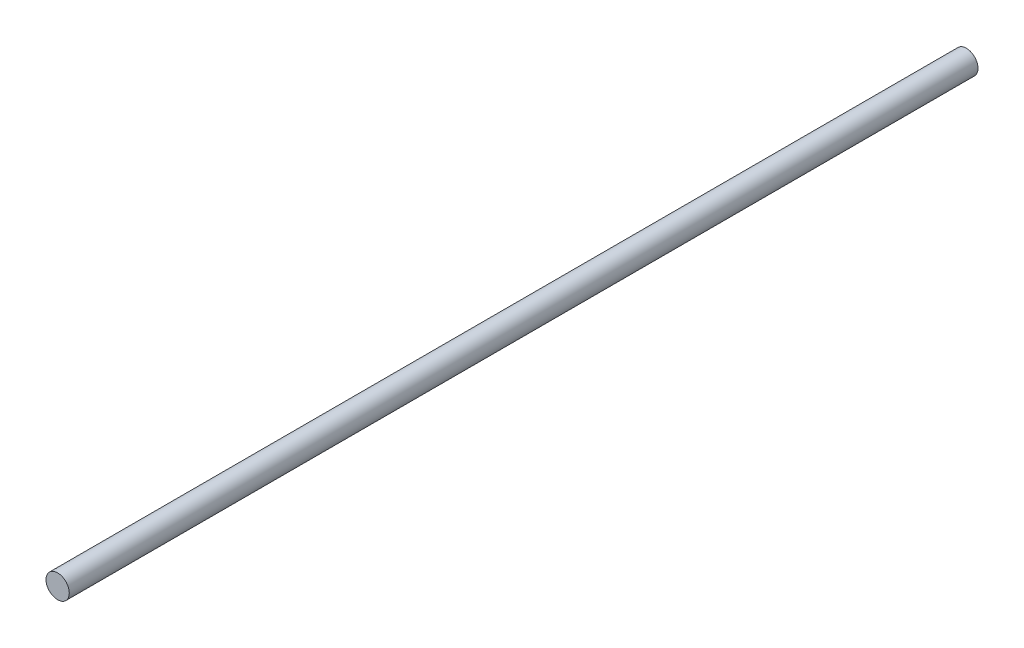
SolidWorks part; units mm, degrees
ref_plane "Plan de face" through (0, 0, 0) normal (0, 0, 1) x (1, 0, 0)
ref_plane "Plan de dessus" through (0, 0, 0) normal (0, 1, 0) x (1, 0, 0)
ref_plane "Plan de droite" through (0, 0, 0) normal (1, 0, 0) x (0, 0, -1)
sketch "Esquisse1" plane through (0, 0, 0) normal (0, 0, 1) x (1, 0, 0)
  circle A0 centre (0, 0) radius 2.5
  dimension "D1" = 5
extrude "Boss.-Extru.1" add sketch "Esquisse1" along normal blind 195
